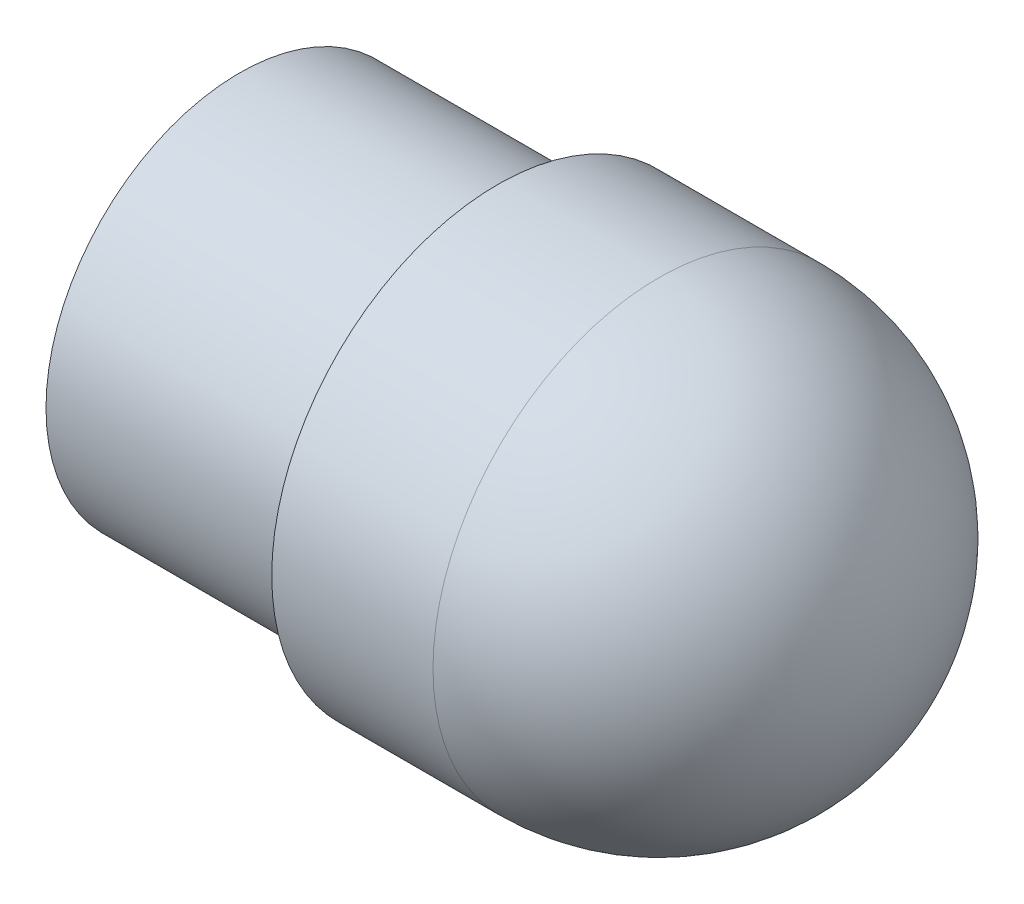
SolidWorks part; units mm, degrees
ref_plane "Plan de face" through (0, 0, 0) normal (0, 0, 1) x (1, 0, 0)
ref_plane "Plan de dessus" through (0, 0, 0) normal (0, 1, 0) x (1, 0, 0)
ref_plane "Plan de droite" through (0, 0, 0) normal (1, 0, 0) x (0, 0, -1)
sketch "Esquisse1" plane through (0, 0, 0) normal (0, 0, 1) x (1, 0, 0)
  line L0 (-59.506, 0) -> (589.1469, 0) construction
  line L1 (-27.1476, 0) -> (-27.1476, -150)
  line L2 (-27.1476, -150) -> (172.8524, -150)
  line L3 (172.8524, -150) -> (172.8524, 0)
  line L4 (172.8524, 0) -> (-27.1476, 0)
  line L5 (172.8524, -150) -> (172.8524, -175)
  line L6 (172.8524, -175) -> (297.8524, -175)
  line L7 (297.8524, -175) -> (297.8524, 0)
  line L8 (297.8524, 0) -> (172.8524, 0)
  line L9 (297.8524, 0) -> (472.8524, 0)
  arc A0 (297.8524, -175) -> (472.8524, 0) centre (297.8524, 0) ccw
  dimension "D4" = 175
  dimension "D1" = 150
  dimension "D2" = 200
  dimension "D3" = 27.1476
  dimension "D5" = 500
revolve "Révolution1" add sketch "Esquisse1" angle 360 about L0
